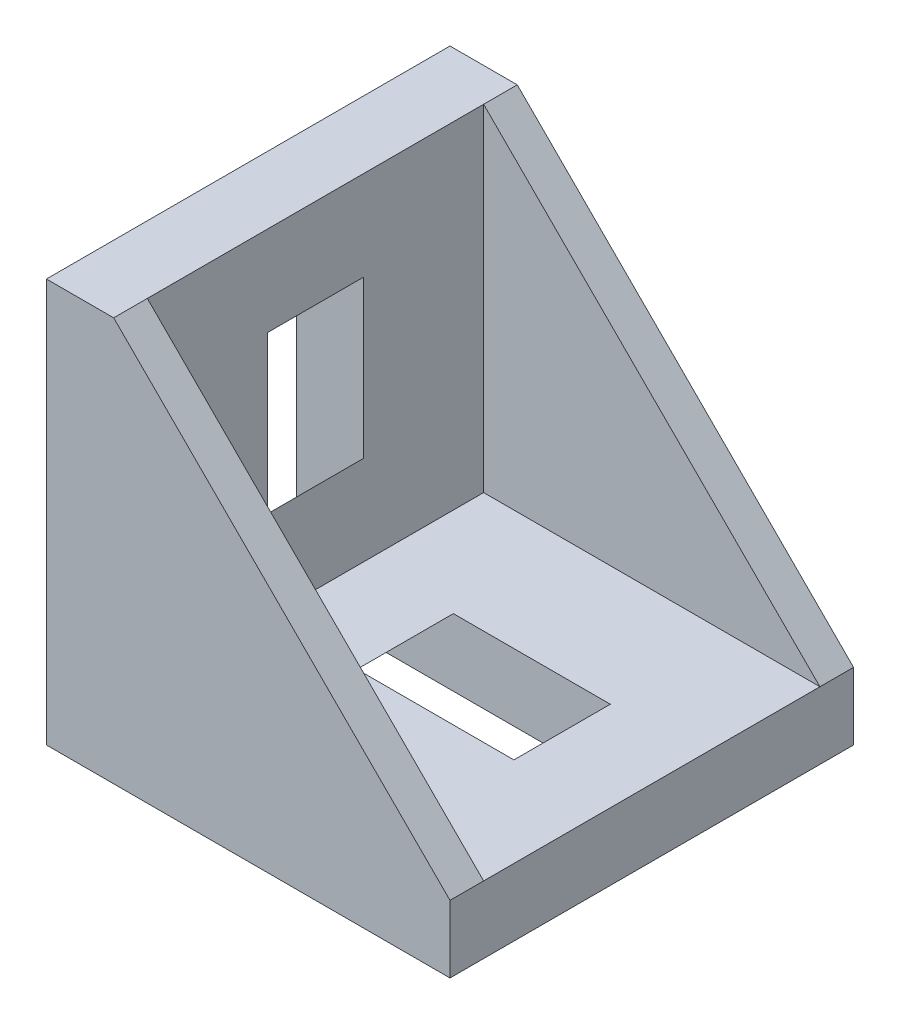
SolidWorks part; units mm, degrees
ref_plane "Front Plane" through (0, 0, 0) normal (0, 0, 1) x (1, 0, 0)
ref_plane "Top Plane" through (0, 0, 0) normal (0, 1, 0) x (1, 0, 0)
ref_plane "Right Plane" through (0, 0, 0) normal (1, 0, 0) x (0, 0, -1)
sketch "Sketch1" plane through (0, 0, 0) normal (0, 0, 1) x (1, 0, 0)
  line L0 (0, 0) -> (0, 18)
  line L1 (18, 3) -> (3, 18)
  line L4 (3, 18) -> (0, 18)
  line L5 (18, 0) -> (0, 0)
  line L7 (18, 3) -> (18, 0)
  dimension "D" = 3
  dimension "C" = 18
  dimension "B" = 18
extrude "Boss-Extrude1" add sketch "Sketch1" along normal mid plane 18
sketch "Sketch2" plane through (0, 0, 0) normal (0, 0, 1) x (1, 0, 0)
  line L0 (3, 18) -> (3, 3)
  line L1 (3, 3) -> (18, 3)
  line L2 (3, 18) -> (18, 3)
extrude "Cut-Extrude1" cut sketch "Sketch2" against normal mid plane 15
sketch "Sketch3" plane through (0, 0, 0) normal (0, 0, 1) x (1, 0, 0)
  line L0 (18, 3) -> (3, 18) construction
  line L1 (0, 14) -> (3, 14)
  line L2 (0, 14) -> (0, 4)
  line L3 (0, 4) -> (3, 7)
  line L4 (3, 14) -> (3, 7)
  line L5 (7, 3) -> (14, 3)
  line L6 (7, 3) -> (4, 0)
  line L7 (4, 0) -> (14, 0)
  line L8 (14, 3) -> (14, 0)
  line L9 (3, 18) -> (0, 18) construction
  line L10 (18, 0) -> (0, 0) construction
  line L11 (0, 0) -> (0, 18) construction
  line L12 (18, 0) -> (18, 3) construction
  dimension "D1" = 14
  dimension "D2" = 7
  dimension "D3" = 14
  dimension "D4" = 7
  dimension "D5" = 4
  dimension "D6" = 4
extrude "Cut-Extrude2" cut sketch "Sketch3" against normal mid plane 4.3
sketch "Sketch4" plane through (0, 0, 0) normal (0, 0, 1) x (1, 0, 0)
  line L0 (0, 18) -> (0, 0) construction
  line L1 (1.2115, 2.3429) -> (0, 1.2348) construction
  line L2 (1.5046, -1.8) -> (0.5112, -0.7909)
  line L3 (0, 3.5355) -> (-1.8, 1.5046)
  line L4 (-1.8, 1.5046) -> (-0.7909, 0.5112)
  line L5 (-0.7909, 0.5112) -> (0, 1.2348)
  line L6 (0, 1.2348) -> (0, 3.5355)
  line L7 (0.5112, -0.7909) -> (1.2348, 0)
  line L8 (0, 0) -> (0, 18) construction
  line L9 (-1.2955, 1.0079) -> (0, 2.3239) construction
  line L10 (1.2348, 0) -> (3.5355, 0)
  line L11 (3.5355, 0) -> (1.5046, -1.8)
  line L12 (0, 17.3) -> (0, 14.9992)
  line L13 (0, 14.9992) -> (-0.7909, 14.2757)
  line L14 (-0.7909, 14.2757) -> (-1.8, 15.269)
  line L15 (-1.8, 15.269) -> (0, 17.3)
  line L16 (-1.2955, 14.7724) -> (0, 16.0884) construction
  line L17 (0, 16.0884) -> (0.6057, 16.7037) construction
  line L18 (18, 3) -> (3, 18) construction
  line L19 (10.5, 10.5) -> (0, 0) construction
  line L20 (0, 17.3) -> (1.2115, 16.1074) construction
  line L21 (0, 14.9992) -> (1.2115, 16.1074) construction
  line L22 (0, 3.5355) -> (1.2115, 2.3429) construction
  line L23 (14.9992, 0) -> (14.2757, -0.7909)
  line L24 (0.6057, 2.9392) -> (0, 2.3239) construction
  line L25 (14.2757, -0.7909) -> (15.269, -1.8)
  line L26 (17.3, 0) -> (14.9992, 0)
  line L27 (15.269, -1.8) -> (17.3, 0)
  line L28 (-1.8, 1.5046) -> (-1.8, 15.269) construction
  dimension "D1" = 1.7
  dimension "D2" = 5
  dimension "D3" = 6
  dimension "D4" = 1.6001
  dimension "D5" = 0.7
  dimension "D6" = 0.1905
  dimension "D7" = 1.8
